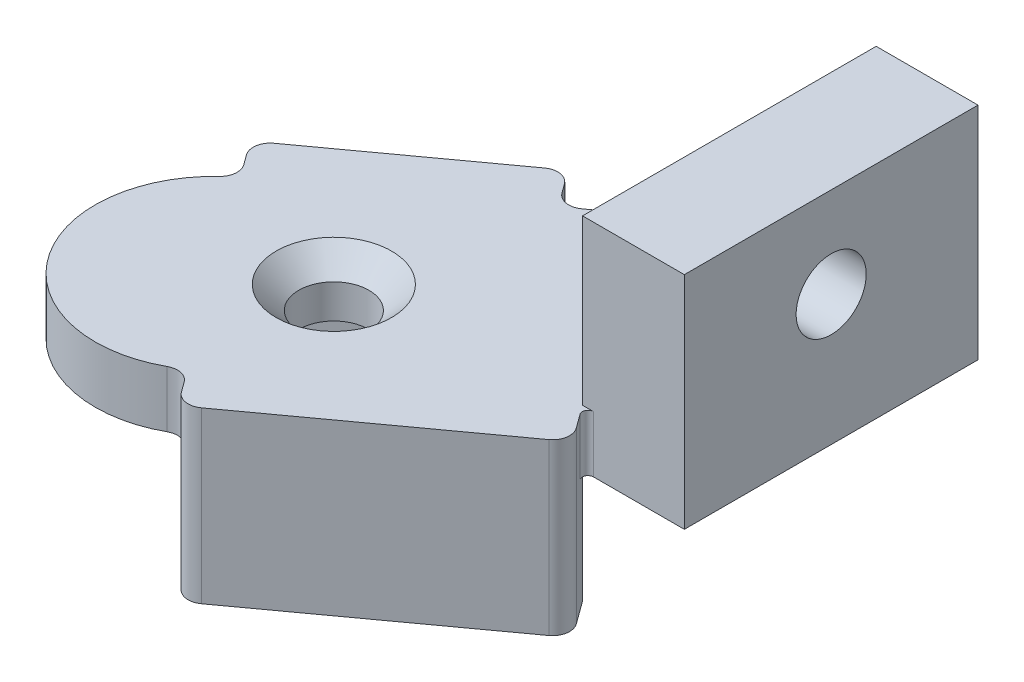
SolidWorks part; units mm, degrees
material "PA 类型 6"
ref_plane "前视基准面" through (0, 0, 0) normal (0, 0, 1) x (1, 0, 0)
ref_plane "上视基准面" through (0, 0, 0) normal (0, 1, 0) x (1, 0, 0)
ref_plane "右视基准面" through (0, 0, 0) normal (1, 0, 0) x (0, 0, -1)
sketch "草图1" plane through (0, 0, 0) normal (0, 1, 0) x (1, 0, 0)
  line L0 (0, 0) -> (0, 12.2017) construction
  line L1 (0, 0) -> (15.21, 0) construction
  line L2 (0, 0) -> (11.3188, 8.2236) construction
  line L3 (10.1244, 13.8452) -> (-6.1542, 2.018)
  line L4 (10.1244, 0.8664) -> (0.0175, -6.4766)
  line L5 (0.0175, -6.4766) -> (-6.1542, 2.018) construction
  line L6 (10.1244, 13.8452) -> (10.1244, 0.8664)
  circle A0 centre (0, 0) radius 1.55
  arc A1 (-6.1542, 2.018) -> (0.0175, -6.4766) centre (-3.0684, -2.2293) ccw
  dimension "D1" = 3.1
  dimension "D2" = 36
  dimension "D3" = 10.5
  dimension "D4" = 10.1244
extrude "基座" add sketch "草图1" along normal blind 2.5
sketch "草图2" plane through (0, 0, 0) normal (0, 1, 0) x (1, 0, 0)
  line L0 (0.0175, -6.4766) -> (1.1931, -8.0947)
  line L1 (1.1931, -8.0947) -> (11.3, -0.7516)
  line L2 (11.3, -0.7516) -> (10.1244, 0.8664)
  line L3 (0.0175, -6.4766) -> (10.1244, 0.8664) construction
  line L4 (10.1244, 0.8664) -> (0.0175, -6.4766)
  line L5 (0, 0) -> (19.4408, 0) construction
  line L6 (0, 0) -> (14.65, 10.6439) construction
  line L7 (10.1244, 13.8452) -> (-6.1542, 2.018) construction
  line L8 (10.1244, 13.8452) -> (-6.1542, 2.018) construction
  line L10 (-7.3298, 3.6361) -> (0.8095, 9.5496)
  line L11 (-6.1542, 2.018) -> (-7.3298, 3.6361)
  line L12 (1.9851, 7.9316) -> (-6.1542, 2.018)
  line L13 (0.8095, 9.5496) -> (1.9851, 7.9316)
  point P20 (1.9851, 7.9316)
  dimension "D1" = 2
extrude "机臂限位" add sketch "草图2" against normal blind 7.5 from surface at 2.5 starting at face at (2.4662, 2.5, -1.7918)
sketch "草图3" plane through (0, 0, 0) normal (0, 1, 0) x (1, 0, 0)
  line L0 (10.1244, 13.8452) -> (14.6244, 13.8452)
  line L1 (14.6244, 13.8452) -> (14.6244, 0.8664)
  line L2 (14.6244, 0.8664) -> (10.1244, 0.8664)
  line L3 (10.1244, 0.8664) -> (10.1244, 13.8452)
  dimension "D1" = 4.5
extrude "限位-1" add sketch "草图3" along normal blind 9.75
sketch "草图4" plane through (0, 0, 0) normal (0, 0, 1) x (1, 0, 0)
  line L0 (14.6244, 9.75) -> (21.1244, 9.75)
  line L1 (21.1244, 9.75) -> (21.1244, -2.25)
  line L2 (21.1244, -2.25) -> (17.6244, -2.25)
  line L3 (17.6244, -2.25) -> (17.6244, 6.5)
  line L4 (17.6244, 6.5) -> (14.6244, 6.5)
  line L5 (14.6244, 9.75) -> (14.6244, 0) construction
  line L6 (14.6244, 6.5) -> (14.6244, 9.75)
  dimension "D1" = 3.25
  dimension "D2" = 3
  dimension "D3" = 8.75
  dimension "D4" = 3.5
chamfer "倒角1" distance 1 angle 45 1 edges at (0, 2.5, 1.55)
sketch "草图5" plane through (10.1244, 0, 0) normal (-1, 0, 0) x (0, 0, 1)
  line L0 (-3.6361, 2.5) -> (-9.5496, 2.5) construction
  line L1 (-4.1515, 5.755) -> (-5.7537, 8.53)
  line L2 (-5.7537, 8.53) -> (-8.9579, 8.53)
  line L3 (-8.9579, 8.53) -> (-10.5601, 5.755)
  line L4 (-10.5601, 5.755) -> (-8.9579, 2.98)
  line L5 (-8.9579, 2.98) -> (-5.7537, 2.98)
  line L6 (-5.7537, 2.98) -> (-4.1515, 5.755)
  line L7 (-7.3558, 10.4317) -> (-7.3558, 1.4425) construction
  line L8 (-13.8452, 9.75) -> (-0.8664, 9.75) construction
  circle A0 centre (-7.3558, 5.755) radius 2.775 construction
  point P14 (-7.3558, 9.75)
  dimension "D1" = 0.48
  dimension "D2" = 5.55
extrude "螺母" cut sketch "草图5" against normal blind 2
sketch "草图6" plane through (10.1244, 0, 0) normal (-1, 0, 0) x (0, 0, 1)
  line L1 (-7.3558, 5.755) -> (-7.3558, 7.9196) construction
  line L2 (-5.7537, 8.53) -> (-8.9579, 8.53) construction
  circle A0 centre (-7.3558, 5.755) radius 1.55
  point P4 (-7.3558, 8.53)
  dimension "D1" = 3.1
extrude "M3螺孔" cut sketch "草图6" against normal up to next
fillet "圆角5" radius 0.75 7 edges at (1.1931, -1.25, 8.0947) (-7.3298, -1.25, -3.6361) (0.0175, 1.25, 6.4766) (-6.1542, 1.25, -2.018) (11.3, -1.25, 0.7516) (1.9851, 1.25, -7.9316) (0.8095, -1.25, -9.5496)
fillet "圆角6" radius 0.25 1 edges at (10.1244, 1.25, -0.8664)
